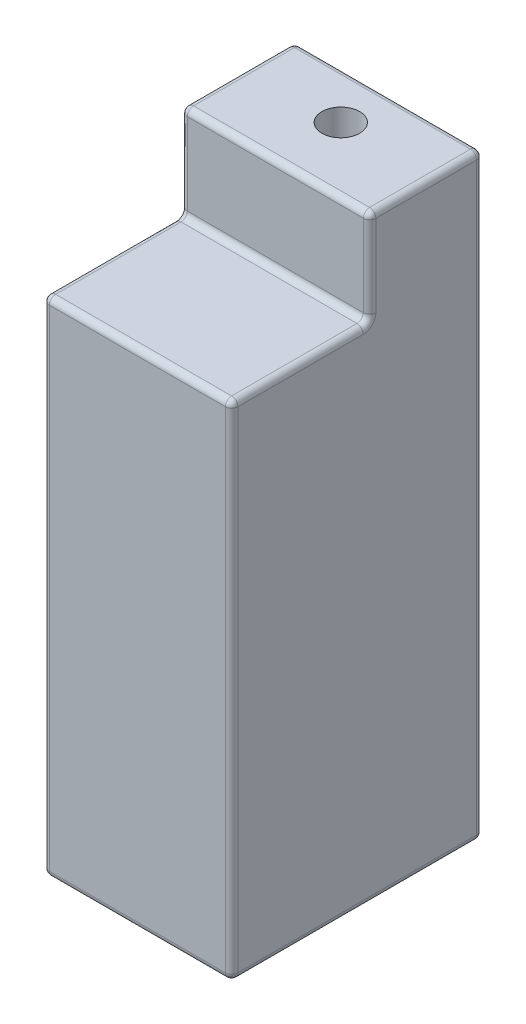
SolidWorks part; units mm, degrees
ref_plane "Front Plane" through (0, 0, 0) normal (0, 0, 1) x (1, 0, 0)
ref_plane "Top Plane" through (0, 0, 0) normal (0, 1, 0) x (1, 0, 0)
ref_plane "Right Plane" through (0, 0, 0) normal (1, 0, 0) x (0, 0, -1)
sketch "Sketch1" plane through (0, 0, 0) normal (0, 0, 1) x (1, 0, 0)
  line L1 (-150, 400) -> (150, 400)
  line L2 (-150, 400) -> (-150, -400)
  line L3 (-150, -400) -> (150, -400)
  line L4 (150, 400) -> (150, -400)
  line L5 (0, -400) -> (0, 400) construction
  line L6 (-150, 0) -> (150, 0) construction
  point P0 (0, 0)
  dimension "D1" = 800
  dimension "D2" = 300
extrude "Boss-Extrude1" add sketch "Sketch1" along normal blind 400
sketch "Sketch3" plane through (0, 400, 0) normal (0, 1, 0) x (1, 0, 0)
  line L0 (150, -400) -> (150, 0) construction
  line L1 (-150, 0) -> (150, 0)
  line L2 (-150, 0) -> (-150, -180.4267)
  line L3 (-150, -180.4267) -> (150, -180.4267)
  line L4 (150, 0) -> (150, -180.4267)
extrude "Boss-Extrude4" add sketch "Sketch3" along normal blind 150
fillet "Fillet6" radius 10 18 edges at (0, 550, 0) (0, -400, 0) (150, -400, 200) (150, 550, 90.2134) (150, 75, 0) (150, 400, 290.2134) (0, 550, 180.4267) (150, 475, 180.4267) (0, 400, 180.4267) (0, -400, 400) (0, 400, 400) (150, 0, 400) (-150, 550, 90.2134) (-150, 475, 180.4267) (-150, 400, 290.2134) (-150, 0, 400) (-150, -400, 200) (-150, 75, 0)
sketch "Sketch4" plane through (0, 550, 0) normal (0, 1, 0) x (1, 0, 0)
  circle A0 centre (0, -76.2197) radius 30
extrude "Cut-Extrude1" cut sketch "Sketch4" against normal blind 150
sketch "Sketch7" plane through (0, 0, 0) normal (0, 0, -1) x (-1, 0, 0)
  line L1 (-125.71, 222.9065) -> (125.71, 222.9065)
  line L2 (-125.71, 222.9065) -> (-125.71, -222.9065)
  line L3 (-125.71, -222.9065) -> (125.71, -222.9065)
  line L4 (125.71, 222.9065) -> (125.71, -222.9065)
  line L5 (0, -222.9065) -> (0, 222.9065) construction
  line L6 (-125.71, 0) -> (125.71, 0) construction
  point P0 (0, 0)
extrude "Cut-Extrude5" cut sketch "Sketch7" against normal blind 170
sketch "Sketch8" plane through (0, -400, 0) normal (0, -1, 0) x (1, 0, 0)
  circle A0 centre (0, 200) radius 40
  dimension "D1" = 80
extrude "Cut-Extrude6" cut sketch "Sketch8" against normal blind 80
fillet "Fillet8" radius 10 4 edges at (125.71, 0, 0) (0, -222.9065, 0) (-125.71, 0, 0) (0, 222.9065, 0)
